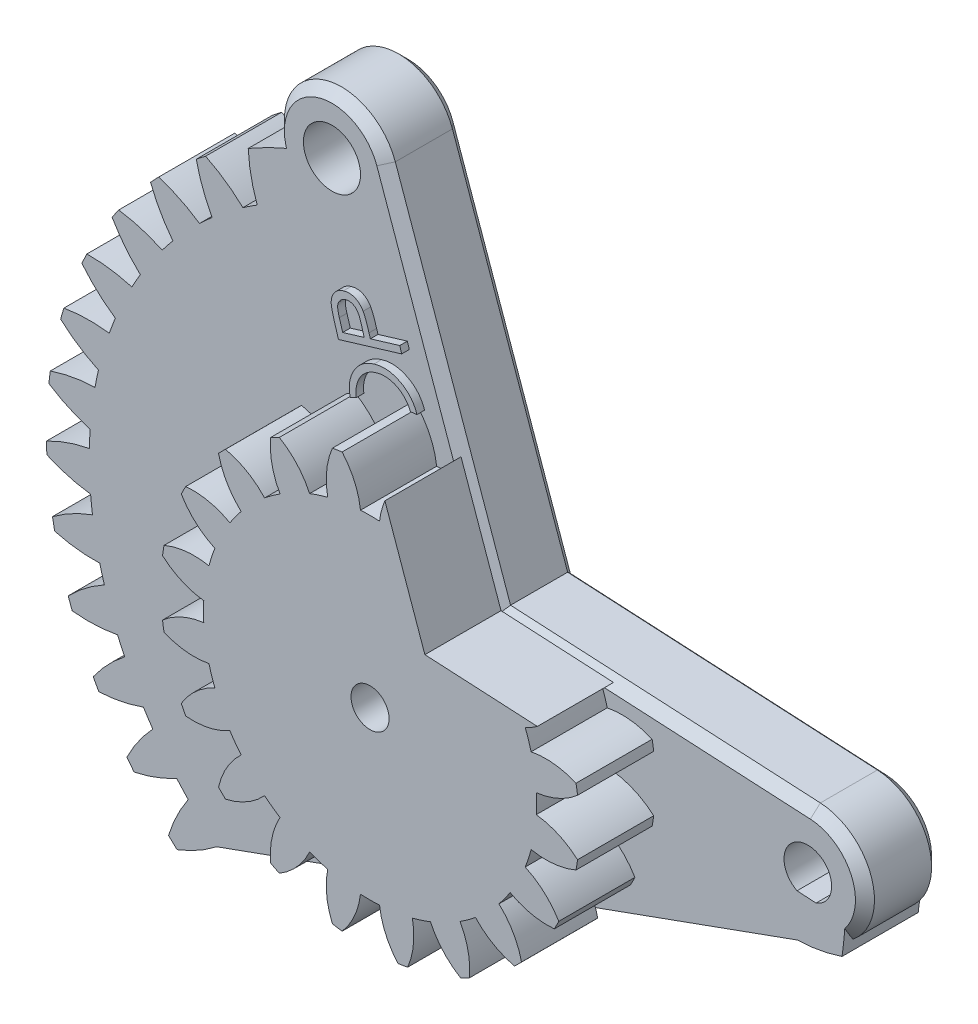
SolidWorks part; units mm, degrees
ref_plane "Alzado" through (0, 0, 0) normal (0, 0, 1) x (1, 0, 0)
ref_plane "Planta" through (0, 0, 0) normal (0, 1, 0) x (1, 0, 0)
ref_plane "Vista lateral" through (0, 0, 0) normal (1, 0, 0) x (0, 0, -1)
sketch "Croquis1" plane through (0, 0, 0) normal (0, 0, 1) x (1, 0, 0)
  line L0 (0, 0) -> (16185.8284, 0) construction
  line L1 (0, 0) -> (19, 0) construction
  line L2 (0.2105, 3.9945) -> (19.1579, 2.9958)
  line L3 (0.2105, -3.9945) -> (19.1579, -2.9958)
  circle A0 centre (0, 0) radius 1.5
  circle A1 centre (19, 0) radius 1.25
  arc A3 (19.1579, -2.9958) -> (19.1579, 2.9958) centre (19, 0) ccw
  arc A4 (0.2105, 3.9945) -> (0.2105, -3.9945) centre (0, 0) ccw
  point P5 (9.5, 0)
  dimension "D2" = 3
  dimension "D3" = 2.5
  dimension "D4" = 3
  dimension "D5" = 8
  dimension "D1" = 19
extrude "Saliente-Extruir1" add sketch "Croquis1" along normal blind 4
sketch "Croquis2" plane through (0, 0, 4) normal (0, 0, 1) x (1, 0, 0)
  line L6 (-3.1711, 20.9987) -> (3.7719, 1.3316)
  line L7 (-8.9115, 19.2766) -> (-3.882, -0.9646)
  circle A1 centre (0, 0) radius 2.0347
  circle A2 centre (-6, 20) radius 1.5
  arc A3 (-3.1711, 20.9987) -> (-8.9115, 19.2766) centre (-6, 20) ccw
  arc A4 (-3.882, -0.9646) -> (3.7719, 1.3316) centre (0, 0) ccw
  dimension "D1" = 3
  dimension "D2" = 3
  dimension "D3" = 20
  dimension "D4" = 6
extrude "Saliente-Extruir2" add sketch "Croquis2" against normal through all
chamfer "Chaflán1" distance 0.5 angle 45 14 edges at (9.6842, -3.4951, 0) (9.6842, -3.4951, 4) (22, 0, 0) (22, 0, 4) (11.0197, 3.4248, 0) (11.0197, 3.4248, 4) (-2.3801, -3.2148, 4) (-2.3801, -3.2148, 0) (-0.1448, 12.4262, 0) (-6.862, 22.8735, 0) (-6.3967, 9.156, 0) (-0.1448, 12.4262, 4) (-6.862, 22.8735, 4) (-6.3967, 9.156, 4)
sketch "Croquis11" plane through (0, 0, 4) normal (0, 0, 1) x (1, 0, 0)
  line L0 (0, 6.9104) -> (-3.2355, 17.6194) construction
  text T0 "TOP"
extrude "Saliente-Extruir5" add sketch "Croquis11" along normal blind 0.4
sketch "Croquis5" plane through (0, 0, 4) normal (0, 0, 1) x (1, 0, 0)
  line L0 (-8.1254, 19.3643) -> (-0.3869, 0.9221)
  line L1 (0.9982, -0.0603) -> (20.9618, -1.2661)
  arc A0 (20.9618, -1.2661) -> (-8.1254, 19.3643) centre (0, 0) cw
  arc A1 (-0.3869, 0.9221) -> (0.9982, -0.0603) centre (0, 0) ccw
  dimension "D1" = 21
extrude "Saliente-Extruir3" add sketch "Croquis5" against normal through all
sketch "Croquis4" plane through (0, 0, 0) normal (0, 0, 1) x (1, 0, 0)
  line L1 (0, 0) -> (-58.6438, 89.1281) construction
  line L2 (0, 0) -> (-11.6947, 16.2245) construction
  line L3 (0, 0) -> (-24.5246, 31.5671) construction
  line L4 (-11.6947, 16.2245) -> (-12.2623, 15.7835) construction
  arc A0 (-9.9278, 15.9048) -> (-10.6775, 15.4116) centre (0, 0) ccw
  arc A1 (-10.4011, 18.2725) -> (-12.6646, 16.7832) centre (0, 0) ccw
  circle A2 centre (0, 0) radius 20 construction
  circle A3 centre (0, 0) radius 18.7939 construction
  arc A4 (-10.6775, 15.4116) -> (-12.6646, 16.7832) centre (-16.1636, 9.589) ccw
  arc A5 (-10.4011, 18.2725) -> (-9.9278, 15.9048) centre (-2.4095, 18.6388) ccw
  dimension "Root_dia" = 37.498
  dimension "Overcut_dia" = 42.0508
  dimension "Pitch_dia" = 40
  dimension "Base_dia" = 37.5877
  dimension "Flank_rad" = 8
  dimension "Half_ang" = 4.5
  dimension "Half_CT" = 0.7187
extrude "Cortar-Extruir1" cut sketch "Croquis4" along normal blind 10
pattern_circular "MatrizC1" count 26 every 9 about axis through (0, 0, 0) along (0, 0, 1) of "Cortar-Extruir1"
sketch "Croquis9" plane through (0, 0, 4) normal (0, 0, 1) x (1, 0, 0)
  line L0 (-12.0585, -14.3568) -> (18.4477, -3.3475)
  line L1 (18.4477, -3.3475) -> (41.7926, -9.999)
  line L2 (41.7926, -9.999) -> (3.3305, -34.9293)
  line L3 (3.3305, -34.9293) -> (-27.1251, -28.4282)
  line L4 (-27.1251, -28.4282) -> (-12.0585, -14.3568)
extrude "Cortar-Extruir3" cut sketch "Croquis9" against normal blind 10
sketch "Croquis7" plane through (0, 0, 4) normal (0, 0, 1) x (1, 0, 0)
  circle A0 centre (0, 0) radius 11
  circle A1 centre (0, 0) radius 1
  dimension "D1" = 22
extrude "Saliente-Extruir4" add sketch "Croquis7" along normal blind 4
sketch "Croquis8" plane through (0, 0, 8) normal (0, 0, 1) x (1, 0, 0)
  line L1 (0, 0) -> (0, 107) construction
  line L2 (0, 0) -> (-0.8511, 9.9637) construction
  line L3 (0, 0) -> (-3.1206, 19.7028) construction
  line L4 (-0.8511, 9.9637) -> (-1.5603, 9.8514) construction
  arc A0 (0.4999, 8.7347) -> (-0.4999, 8.7347) centre (0, 0) ccw
  arc A1 (1.4852, 10.9249) -> (-1.4852, 10.9249) centre (0, 0) ccw
  circle A2 centre (0, 0) radius 10 construction
  circle A3 centre (0, 0) radius 9.3969 construction
  arc A4 (-0.4999, 8.7347) -> (-1.4852, 10.9249) centre (-4.4722, 8.2645) ccw
  arc A5 (1.4852, 10.9249) -> (0.4999, 8.7347) centre (4.4722, 8.2645) ccw
  dimension "Root_dia" = 17.498
  dimension "Overcut_dia" = 22.0508
  dimension "Pitch_dia" = 20
  dimension "Base_dia" = 18.7939
  dimension "Flank_rad" = 4
  dimension "Half_ang" = 9
  dimension "Half_CT" = 0.7181
extrude "Cortar-Extruir2" cut sketch "Croquis8" against normal blind 4
pattern_circular "MatrizC2" count 20 over 360 about axis through (0, 0, 0) along (0, 0, 1) of "Cortar-Extruir2"
sketch "Croquis10" plane through (0, 0, 8) normal (0, 0, 1) x (1, 0, 0)
  line L0 (-3.1711, 20.9987) -> (2.8815, 3.8537)
  line L1 (2.8815, 3.8537) -> (19.1579, 2.9958) construction
  line L2 (-3.1711, 20.9987) -> (2.8815, 3.8537) construction
  line L3 (2.8815, 3.8537) -> (19.1579, 2.9958)
  line L4 (19.1579, 2.9958) -> (14.4803, 14.8756)
  line L5 (14.4803, 14.8756) -> (-3.1711, 20.9987)
extrude "Cortar-Extruir4" cut sketch "Croquis10" against normal through all
